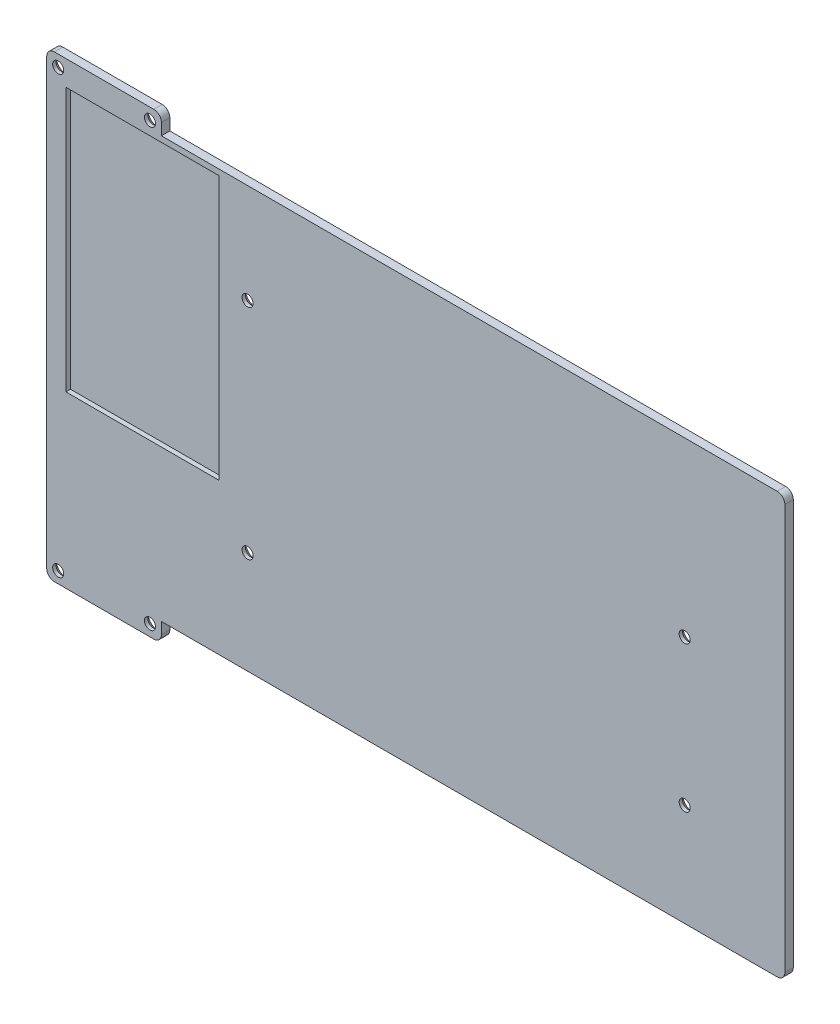
SolidWorks part; units mm, degrees
ref_plane "Front Plane" through (0, 0, 0) normal (0, 0, 1) x (1, 0, 0)
ref_plane "Top Plane" through (0, 0, 0) normal (0, 1, 0) x (1, 0, 0)
ref_plane "Right Plane" through (0, 0, 0) normal (1, 0, 0) x (0, 0, -1)
sketch "Sketch1" plane through (0, 0, 0) normal (0, 0, 1) x (1, 0, 0)
  line L1 (-129.1726, -27.5679) -> (-103.1726, -27.5679)
  line L2 (-131.1726, -25.5679) -> (-131.1726, 90.4321)
  line L3 (-129.1726, 92.4321) -> (-103.1726, 92.4321)
  line L4 (61.8774, -20.5679) -> (61.8774, 85.4321)
  line L9 (59.8774, -22.5679) -> (-101.1726, -22.5679)
  line L12 (-101.1726, -22.5679) -> (-101.1726, -25.5679)
  line L13 (59.8774, 87.4321) -> (-101.1726, 87.4321)
  line L16 (-101.1726, 87.4321) -> (-101.1726, 90.4321)
  arc A0 (-129.1726, -27.5679) -> (-131.1726, -25.5679) centre (-129.1726, -25.5679) cw
  arc A3 (-131.1726, 90.4321) -> (-129.1726, 92.4321) centre (-129.1726, 90.4321) cw
  arc A4 (59.8774, -22.5679) -> (61.8774, -20.5679) centre (59.8774, -20.5679) ccw
  arc A5 (59.8774, 87.4321) -> (61.8774, 85.4321) centre (59.8774, 85.4321) cw
  arc A6 (-103.1726, 92.4321) -> (-101.1726, 90.4321) centre (-103.1726, 90.4321) cw
  arc A7 (-103.1726, -27.5679) -> (-101.1726, -25.5679) centre (-103.1726, -25.5679) ccw
  point P6 (-131.1726, -27.5679)
  point P7 (61.8774, -22.5679)
  point P9 (61.8774, -27.5679)
  point P12 (61.8774, 92.4321)
  point P15 (61.8774, 87.4321)
  point P23 (-101.1726, 92.4321)
  point P26 (-101.1726, -27.5679)
  dimension "D3" = 2
  dimension "D8" = 2
  dimension "D1" = 193.05
  dimension "D2" = 120
  dimension "D4" = 163.05
  dimension "D5" = 5
  dimension "D6" = 163.05
  dimension "D7" = 5
extrude "Boss-Extrude1" add sketch "Sketch1" along normal blind 2.2
hole_wizard "CSK for M2.5 Countersunk Flat Head Screw1" positions "3DSketch1" profile "Sketch2" countersink size "M2.5" standard "ISO" end condition through all
sketch3d "3DSketch1"
  line L1 (61.8774, -20.5679, 0) -> (61.8774, 85.4321, 0) construction
  line L2 (-101.1726, -22.5679, 2.2) -> (59.8774, -22.5679, 2.2) construction
  point P0 (-78.6476, 61.392, 0)
  point P2 (35.6774, 42.342, 0)
  point P4 (35.6774, 4.242, 0)
  point P6 (-78.6476, 4.242, 0)
  dimension "D1" = 26.9
  dimension "D5" = 38.1
  dimension "D2" = 140.525
  dimension "D3" = 114.325
  dimension "D4" = 57.15
sketch "Sketch2" plane through (-78.6476, 61.392, 0) normal (1, 0, 0) x (0, 1, 0)
  line L0 (0, 0) -> (0, 2.2)
  line L1 (0, 2.2) -> (1.45, 2.2)
  line L2 (1.45, 2.2) -> (1.45, 1.3)
  line L3 (1.45, 1.3) -> (2.75, 0)
  line L5 (2.75, 0) -> (0, 0)
  line L6 (-1.45, 1.3) -> (-2.75, 0) construction
  line L11 (0, -6.35) -> (0, 107.95) construction
  dimension "Thru Hole Dia." = 2.9
  dimension "Thru Hole Depth" = 2.2
  dimension "Near C'Sink Dia." = 5.5
  dimension "Near C'Sink Angle" = 90
hole_wizard "CSK for M2.5 Countersunk Flat Head Screw2" positions "3DSketch2" profile "Sketch3" countersink size "M2.5" standard "ISO" end condition through all
sketch3d "3DSketch2"
  line L0 (-103.1726, 92.4321, 0) -> (-129.1726, 92.4321, 0) construction
  line L1 (-101.1726, 87.4321, 0) -> (-101.1726, 90.4321, 0) construction
  line L2 (-131.1726, 90.4321, 0) -> (-131.1726, -25.5679, 0) construction
  line L4 (-129.1726, -27.5679, 0) -> (-103.1726, -27.5679, 0) construction
  point P0 (-104.1726, 89.4321, 0)
  point P2 (-128.1726, 89.4321, 0)
  point P4 (-104.1726, -24.5679, 0)
  point P6 (-128.1726, -24.5679, 0)
  dimension "D1" = 3
  dimension "D2" = 3
  dimension "D3" = 3
  dimension "D4" = 3
sketch "Sketch3" plane through (-104.1726, 89.4321, 0) normal (1, 0, 0) x (0, 1, 0)
  line L0 (0, 0) -> (0, 2.2)
  line L1 (0, 2.2) -> (1.45, 2.2)
  line L2 (1.45, 2.2) -> (1.45, 1.3)
  line L3 (1.45, 1.3) -> (2.75, 0)
  line L5 (2.75, 0) -> (0, 0)
  line L6 (-1.45, 1.3) -> (-2.75, 0) construction
  line L11 (0, -6.35) -> (0, 107.95) construction
  dimension "Thru Hole Dia." = 2.9
  dimension "Thru Hole Depth" = 2.2
  dimension "Near C'Sink Dia." = 5.5
  dimension "Near C'Sink Angle" = 90
sketch "Sketch4" plane through (0, 0, 2.2) normal (0, 0, 1) x (1, 0, 0)
  line L0 (-131.1726, 90.4321) -> (-131.1726, -25.5679) construction
  line L1 (-126.1726, 85.9321) -> (-86.1726, 85.9321)
  line L2 (-126.1726, 85.9321) -> (-126.1726, 16.9321)
  line L3 (-126.1726, 16.9321) -> (-86.1726, 16.9321)
  line L4 (-86.1726, 85.9321) -> (-86.1726, 16.9321)
  line L6 (59.8774, 87.4321) -> (-101.1726, 87.4321) construction
  dimension "D1" = 40
  dimension "D2" = 69
  dimension "D3" = 5
  dimension "D4" = 1.5
extrude "Cut-Extrude1" cut sketch "Sketch4" against normal blind 1.2 and the other way through all
